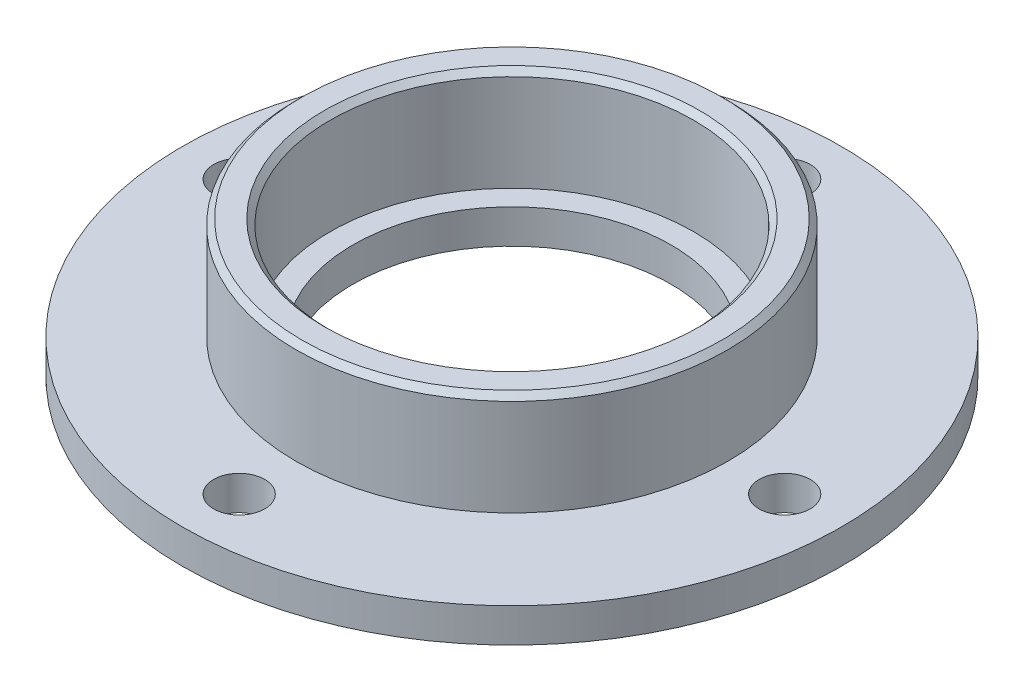
SolidWorks part; units mm, degrees
material "AISI 316 Stainless Steel Sheet (SS)"
ref_plane "Front Plane" through (0, 0, 0) normal (0, 0, 1) x (1, 0, 0)
ref_plane "Top Plane" through (0, 0, 0) normal (0, 1, 0) x (1, 0, 0)
ref_plane "Right Plane" through (0, 0, 0) normal (1, 0, 0) x (0, 0, -1)
sketch "Sketch1" plane through (0, 0, 0) normal (0, 1, 0) x (1, 0, 0)
  line L0 (0, -44.7868) -> (0, 44.7868) construction
  circle A0 centre (0, 0) radius 29
  circle A2 centre (0, 0) radius 14
  circle A3 centre (0, 24) radius 1
  circle A9 centre (24, 0) radius 1
  circle A10 centre (0, -24) radius 1
  circle A11 centre (-24, 0) radius 1
  point P17 (0, 0)
  point P21 (0, 0)
  dimension "D1" = 58
  dimension "D2" = 28
  dimension "D3" = 2
  dimension "D4" = 24
  dimension "D5" = 4
extrude "Boss-Extrude1" add sketch "Sketch1" along normal blind 3
sketch "Sketch2" plane through (0, 3, 0) normal (0, 1, 0) x (1, 0, 0)
  circle A0 centre (0, 0) radius 16
  circle A1 centre (0, 0) radius 19
  dimension "D1" = 32
  dimension "D2" = 38
extrude "Boss-Extrude2" add sketch "Sketch2" along normal blind 9
sketch "Sketch5" plane through (0, 3, 0) normal (0, 1, 0) x (1, 0, 0)
  point P0 (0, 24)
  point P3 (24, 0)
  point P6 (0, -24)
  point P9 (-24, 0)
hole_wizard "M4 Clearance Hole1" positions "Sketch5" profile "Sketch4" hole size "M4" standard "ANSI Metric" end condition through all
sketch "Sketch4" plane through (0, 3, -24) normal (1, 0, 0) x (0, 0, 1)
  line L0 (0, 0) -> (0, 3)
  line L1 (0, 3) -> (2.25, 3)
  line L2 (2.25, 3) -> (2.25, 0)
  line L5 (2.25, 0) -> (0, 0)
  line L11 (0, -6.35) -> (0, 107.95) construction
  dimension "Thru Hole Dia." = 4.5
  dimension "Thru Hole Depth" = 3
chamfer "Chamfer1" distance 0.5 angle 45 2 edges at (0, 12, 19) (0, 12, 16)
